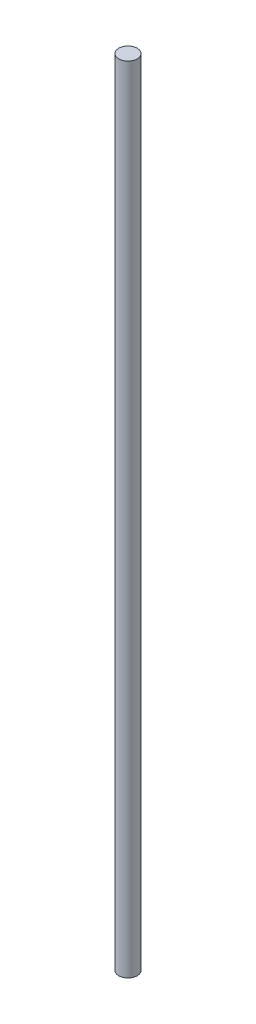
SolidWorks part; units mm, degrees
ref_plane "Front Plane" through (0, 0, 0) normal (0, 0, 1) x (1, 0, 0)
ref_plane "Top Plane" through (0, 0, 0) normal (0, 1, 0) x (1, 0, 0)
ref_plane "Right Plane" through (0, 0, 0) normal (1, 0, 0) x (0, 0, -1)
sketch "Sketch1" plane through (0, 0, 0) normal (0, 1, 0) x (1, 0, 0)
  circle A0 centre (0, 0) radius 3.9878
  dimension "D1" = 7.9756
extrude "Boss-Extrude1" add sketch "Sketch1" along normal blind 342.9
